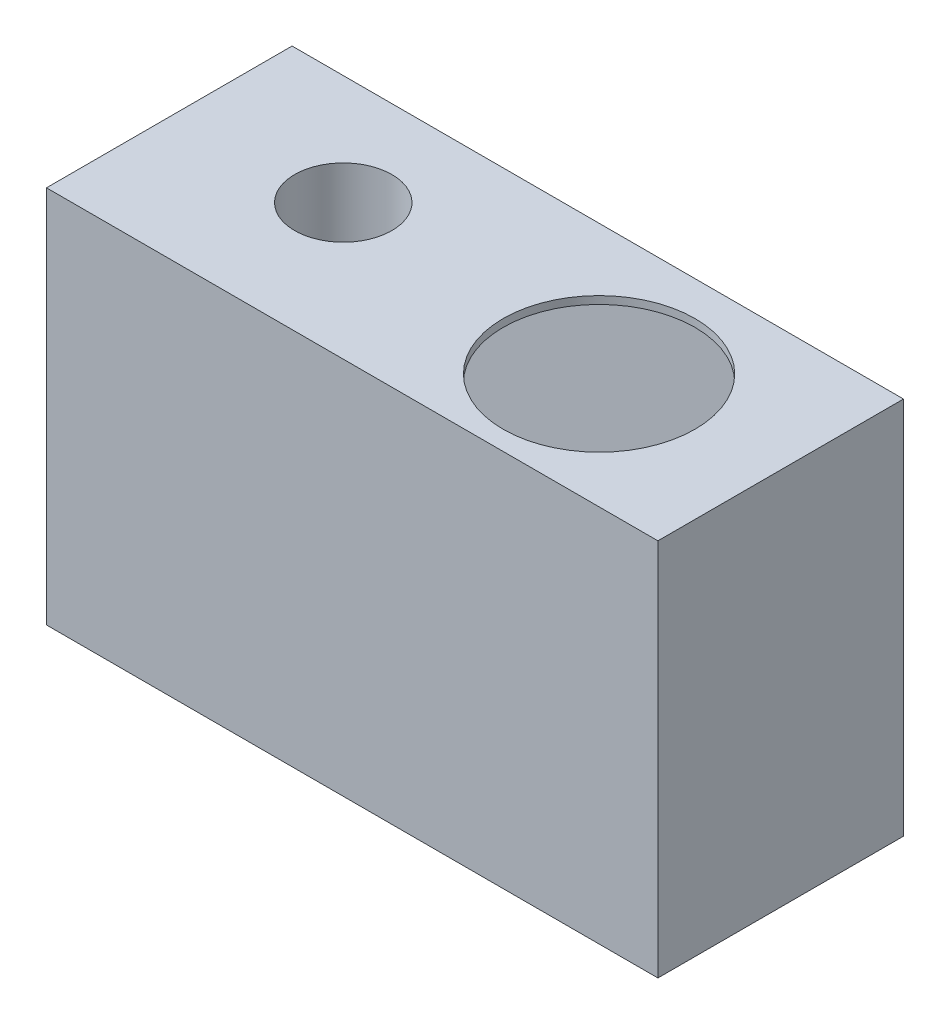
SolidWorks part; units mm, degrees
ref_plane "Front" through (0, 0, 0) normal (0, 0, 1) x (1, 0, 0)
ref_plane "Top" through (0, 0, 0) normal (0, 1, 0) x (1, 0, 0)
ref_plane "Right" through (0, 0, 0) normal (1, 0, 0) x (0, 0, -1)
sketch "Sketch1" plane through (0, 0, 0) normal (0, 1, 0) x (1, 0, 0)
  line L1 (0, 0) -> (239, 0)
  line L2 (0, 0) -> (0, -96)
  line L3 (0, -96) -> (239, -96)
  line L4 (239, 0) -> (239, -96)
  dimension "D1" = 96
  dimension "D2" = 239
extrude "Boss-Extrude1" add sketch "Sketch1" along normal blind 3
sketch "Sketch2" plane through (0, 0, 0) normal (0, -1, 0) x (-1, 0, 0)
  line L0 (-3, -3) -> (-3, -93)
  line L1 (0, 0) -> (-239, 0)
  line L2 (0, 0) -> (0, -96)
  line L3 (0, -96) -> (-239, -96)
  line L4 (-239, 0) -> (-239, -96)
  line L5 (-3, -93) -> (-236, -93)
  line L6 (-236, -3) -> (-236, -93)
  line L7 (-3, -3) -> (-236, -3)
  dimension "D1" = 3
extrude "Boss-Extrude2" add sketch "Sketch2" along normal blind 145
sketch "Sketch3" plane through (0, 0, 0) normal (0, -1, 0) x (-1, 0, 0)
  line L1 (-236, -3) -> (-236, -93) construction
  line L2 (-236, -93) -> (-3, -93) construction
  circle A0 centre (-171, -51) radius 37.5
  dimension "D1" = 75
  dimension "D2" = 65
  dimension "D3" = 42
extrude "Cut-Extrude1" cut sketch "Sketch3" against normal blind 3
sketch "Sketch4" plane through (0, 0, 0) normal (0, -1, 0) x (-1, 0, 0)
  line L0 (-236, -93) -> (-3, -93) construction
  line L1 (-3, -93) -> (-3, -3) construction
  circle A0 centre (-63, -43) radius 19
  dimension "D1" = 38
  dimension "D2" = 50
  dimension "D3" = 60
extrude "Cut-Extrude2" cut sketch "Sketch4" against normal blind 3
sketch "Sketch5" plane through (0, 0, 0) normal (0, -1, 0) x (-1, 0, 0)
  circle A0 centre (-63, -43) radius 19
  circle A1 centre (-63, -43) radius 22
  dimension "D1" = 3
extrude "Boss-Extrude3" add sketch "Sketch5" along normal blind 53
equation "\"D1@Sketch1\"=90+6"
equation "\"D2@Sketch1\"=233+6"
